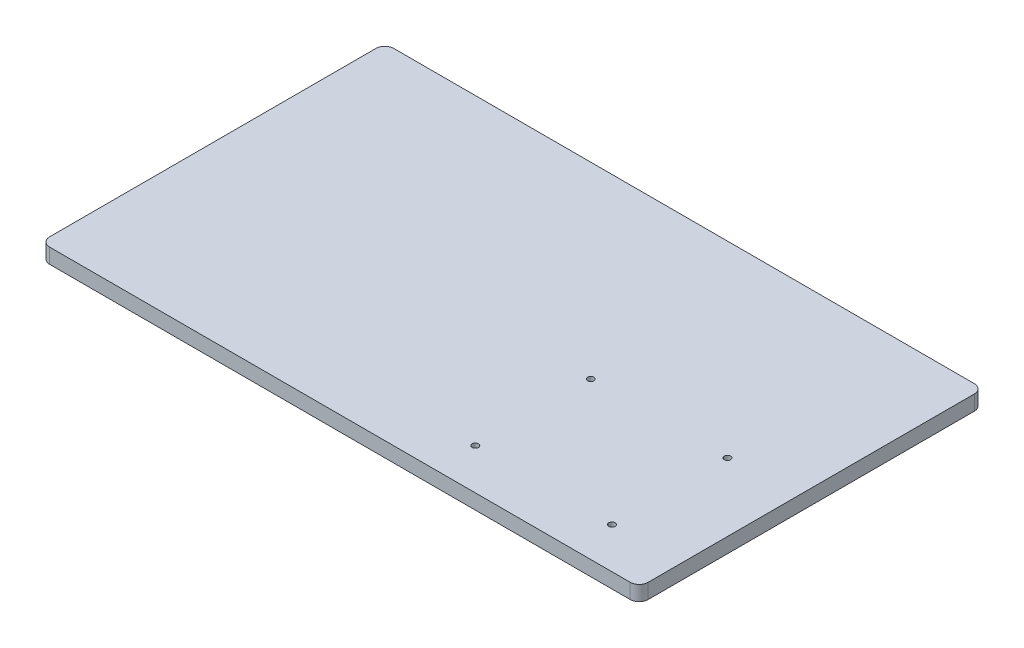
SolidWorks part; units mm, degrees
ref_plane "Front Plane" through (0, 0, 0) normal (0, 0, 1) x (1, 0, 0)
ref_plane "Top Plane" through (0, 0, 0) normal (0, 1, 0) x (1, 0, 0)
ref_plane "Right Plane" through (0, 0, 0) normal (1, 0, 0) x (0, 0, -1)
sketch "Sketch1" plane through (0, 0, 0) normal (0, 1, 0) x (1, 0, 0)
  line L1 (3.81, 0) -> (250.19, 0)
  line L2 (0, 3.81) -> (0, 142.24)
  line L3 (3.81, 146.05) -> (250.19, 146.05)
  line L4 (254, 3.81) -> (254, 142.24)
  arc A0 (250.19, 0) -> (254, 3.81) centre (250.19, 3.81) ccw
  arc A1 (250.19, 146.05) -> (254, 142.24) centre (250.19, 142.24) cw
  arc A2 (0, 142.24) -> (3.81, 146.05) centre (3.81, 142.24) cw
  arc A3 (3.81, 0) -> (0, 3.81) centre (3.81, 3.81) cw
  point P11 (254, 0)
  point P14 (254, 146.05)
  point P17 (0, 146.05)
  point P20 (0, 0)
  dimension "D7" = 3.81
  dimension "D1" = 254
  dimension "D2" = 146.05
extrude "Boss-Extrude1" add sketch "Sketch1" along normal blind 6.35
sketch "Sketch2" plane through (0, 6.35, 0) normal (0, 1, 0) x (1, 0, 0)
  circle A0 centre (167.1, 17.35) radius 1.35
  circle A1 centre (167.1, 66.35) radius 1.35
  circle A2 centre (225.1, 17.35) radius 1.35
  circle A3 centre (225.1, 66.35) radius 1.35
  dimension "D1" = 2.7
  dimension "D2" = 2.7
  dimension "D3" = 2.7
  dimension "D4" = 2.7
extrude "Cut-Extrude1" cut sketch "Sketch2" against normal through all
